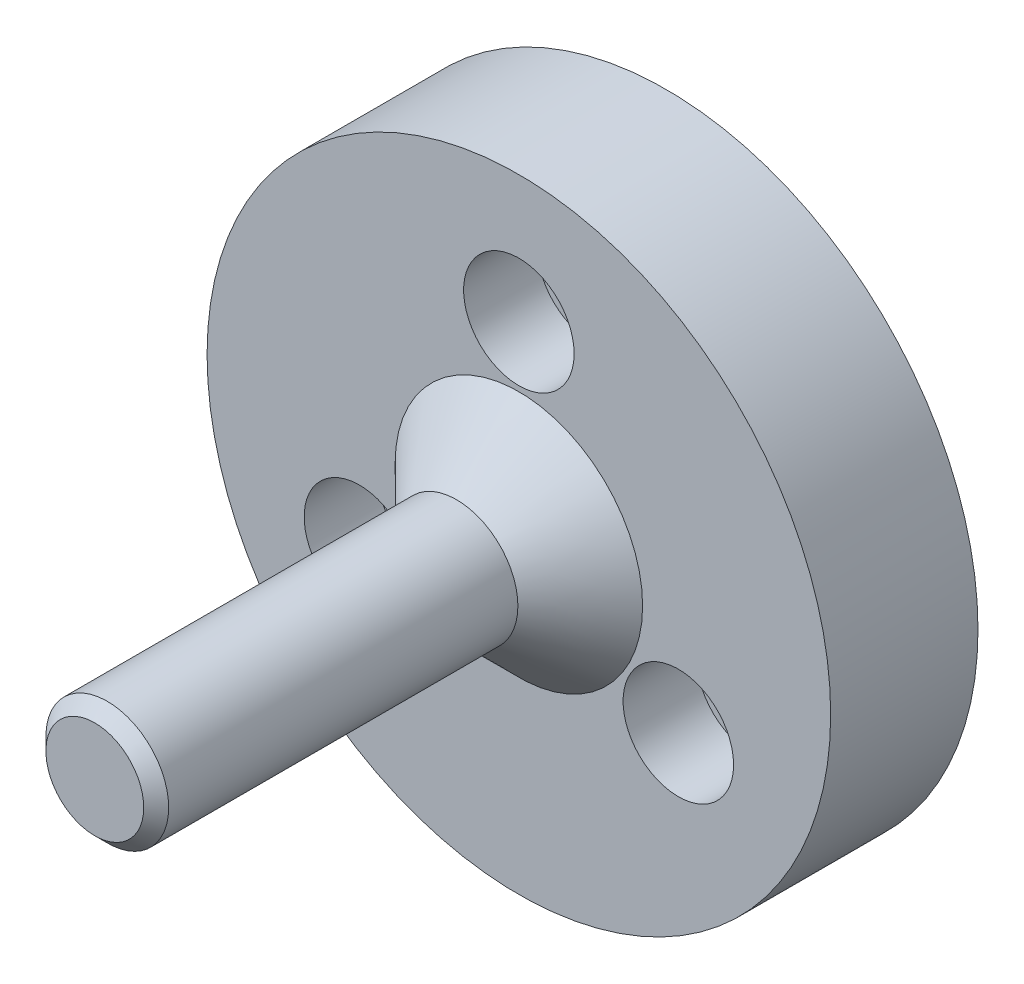
SolidWorks part; units mm, degrees
material "6061 Alloy"
ref_plane "Front Plane" through (0, 0, 0) normal (0, 0, 1) x (1, 0, 0)
ref_plane "Top Plane" through (0, 0, 0) normal (0, 1, 0) x (1, 0, 0)
ref_plane "Right Plane" through (0, 0, 0) normal (1, 0, 0) x (0, 0, -1)
sketch "Sketch1" plane through (0, 0, 0) normal (0, 0, 1) x (1, 0, 0)
  circle A0 centre (0, 0) radius 12.7
  dimension "D2" = 25.4
extrude "Mounting Flange" add sketch "Sketch1" along normal blind 6
sketch "Sketch2" plane through (0, 0, 6) normal (0, 0, 1) x (1, 0, 0)
  circle A0 centre (0, 0) radius 2.5
  dimension "D1" = 5
sketch "Sketch3" plane through (0, 0, 0) normal (0, 0, -1) x (-1, 0, 0)
  circle A0 centre (0, 0) radius 6.35
  dimension "D1" = 12.7
extrude "Motor Shaft Relief" cut sketch "Sketch3" against normal blind 2.54
sketch "Sketch4" plane through (0, 0, 6) normal (0, 0, 1) x (1, 0, 0)
  circle A0 centre (0, 0) radius 7.5 construction
  circle A1 centre (0, 7.5) radius 1.45
  circle A2 centre (6.4952, -3.75) radius 1.45
  circle A3 centre (-6.4952, -3.75) radius 1.45
  point P11 (0, 0)
  dimension "D1" = 15
  dimension "D2" = 2.9
  dimension "D4" = 120
  dimension "D5" = 120
  dimension "D3" = 3
extrude "Screw Clearance Holes" cut sketch "Sketch4" against normal through all
sketch "Sketch6" plane through (0, 0, 6) normal (0, 0, 1) x (1, 0, 0)
  circle A0 centre (0, 7.5) radius 2.25
  circle A1 centre (-6.4952, -3.75) radius 2.25
  circle A2 centre (6.4952, -3.75) radius 2.25
  dimension "D1" = 4.5
  dimension "D2" = 4.5
  dimension "D3" = 4.5
extrude "Screw Head Counterbore" cut sketch "Sketch6" against normal blind 3
extrude "Boss-Extrude1" add sketch "Sketch2" along normal blind 17.272 contours A0
chamfer "Chamfer1" distance 0.508 angle 45 1 edges at (2.5, 0, 23.272)
chamfer "Chamfer2" distance 2.54 angle 45 1 edges at (2.5, 0, 6)
